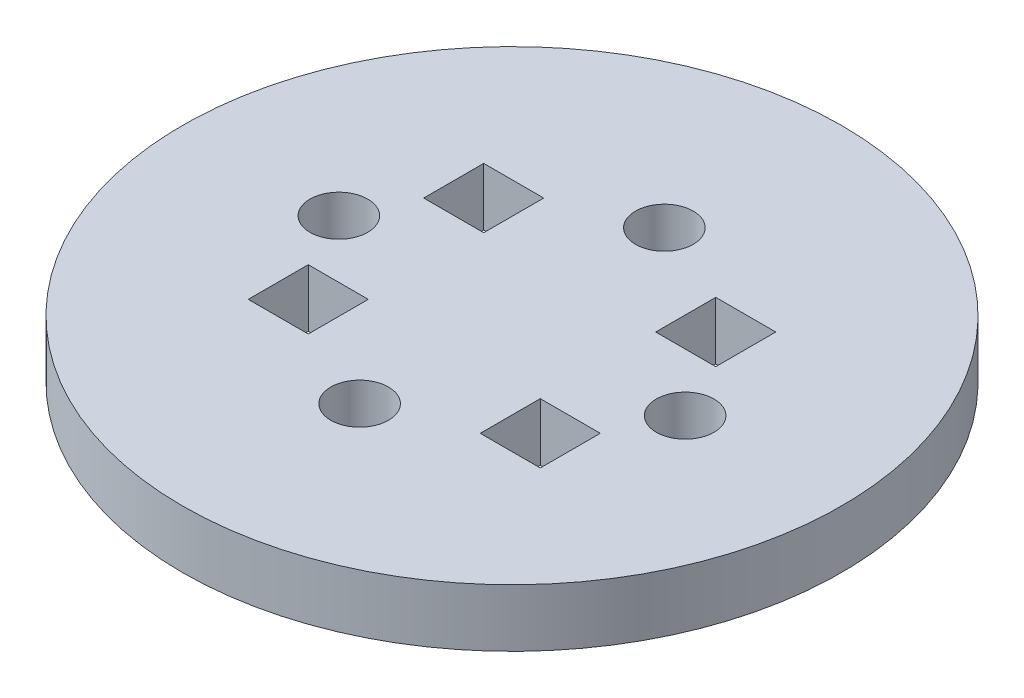
SolidWorks part; units mm, degrees
ref_plane "Front Plane" through (0, 0, 0) normal (0, 0, 1) x (1, 0, 0)
ref_plane "Top Plane" through (0, 0, 0) normal (0, 1, 0) x (1, 0, 0)
ref_plane "Right Plane" through (0, 0, 0) normal (1, 0, 0) x (0, 0, -1)
sketch "Sketch1" plane through (0, 0, 0) normal (0, 1, 0) x (1, 0, 0)
  circle A0 centre (0, 0) radius 36.2585
  circle A1 centre (0, 16.764) radius 3.175
  circle A2 centre (0, -16.764) radius 3.175
  circle A3 centre (-19.05, 0) radius 3.175
  circle A4 centre (19.05, 0) radius 3.175
  dimension "D1" = 72.517
  dimension "D2" = 6.35
  dimension "D3" = 6.35
  dimension "D6" = 6.35
  dimension "D7" = 6.35
  dimension "D4" = 33.528
  dimension "D5" = 16.764
  dimension "D8" = 38.1
  dimension "D9" = 19.05
extrude "Boss-Extrude1" add sketch "Sketch1" along normal blind 6.35
sketch "Sketch2" plane through (0, 6.35, 0) normal (0, 1, 0) x (1, 0, 0)
  line L0 (-16.0655, 12.954) -> (-16.0655, 6.35)
  line L1 (-16.0655, 12.954) -> (-9.4615, 12.954)
  line L3 (-16.0655, -12.954) -> (-9.4615, -12.954)
  line L5 (-16.0655, 6.35) -> (-9.4615, 6.35)
  line L6 (16.0655, 6.35) -> (16.0655, 12.954)
  line L7 (-16.0655, -12.954) -> (-16.0655, -6.35)
  line L8 (-16.0655, -6.35) -> (-9.4615, -6.35)
  line L9 (16.0655, -6.35) -> (16.0655, -12.954)
  line L10 (-9.4615, 12.954) -> (-9.4615, 6.35)
  line L11 (-9.4615, -6.35) -> (-9.4615, -12.954)
  line L12 (9.4615, 12.954) -> (9.4615, 6.35)
  line L13 (9.4615, -6.35) -> (9.4615, -12.954)
  line L14 (9.4615, 12.954) -> (16.0655, 12.954)
  line L15 (9.4615, 6.35) -> (16.0655, 6.35)
  line L16 (9.4615, -6.35) -> (16.0655, -6.35)
  line L17 (9.4615, -12.954) -> (16.0655, -12.954)
  dimension "D1" = 6.604
  dimension "D2" = 6.604
  dimension "D3" = 6.35
  dimension "D4" = 6.35
  dimension "D5" = 6.604
  dimension "D6" = 6.604
  dimension "D7" = 32.131
  dimension "D8" = 32.131
  dimension "D9" = 16.0655
extrude "Cut-Extrude1" cut sketch "Sketch2" against normal blind 10.16
